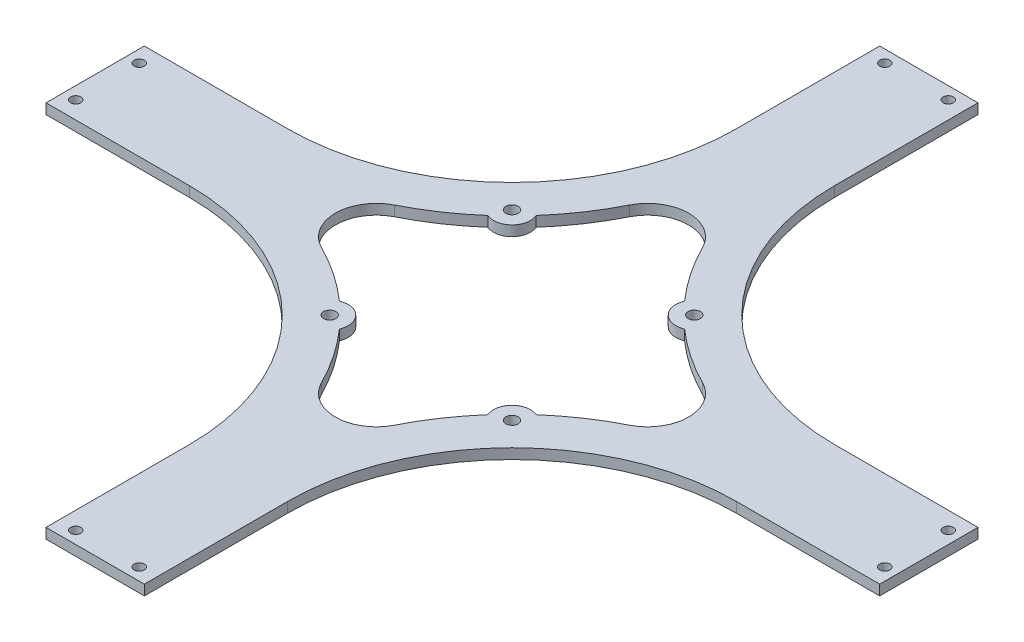
SolidWorks part; units mm, degrees
material "Chipboard"
ref_plane "Front Plane" through (0, 0, 0) normal (0, 0, 1) x (1, 0, 0)
ref_plane "Top Plane" through (0, 0, 0) normal (0, 1, 0) x (1, 0, 0)
ref_plane "Right Plane" through (0, 0, 0) normal (1, 0, 0) x (0, 0, -1)
sketch "Sketch1" plane through (0, 0, 0) normal (0, 1, 0) x (1, 0, 0)
  line L0 (0, 101.75) -> (0, -101.75) construction
  line L1 (-12, 101.75) -> (-12, 66.75)
  line L2 (12, 101.75) -> (12, 66.75)
  line L3 (-101.75, 0) -> (101.75, 0) construction
  line L4 (-101.75, -12) -> (-66.75, -12)
  line L6 (12, 101.75) -> (-12, 101.75)
  line L7 (-12, -66.75) -> (-12, -101.75)
  line L9 (-12, 101.75) -> (-12, -101.75) construction
  line L10 (12, -66.75) -> (12, -101.75)
  line L11 (-101.75, -12) -> (101.75, -12) construction
  line L13 (12, 101.75) -> (12, -101.75) construction
  line L14 (12, 98.75) -> (-12, 98.75) construction
  line L16 (-7.75, 101.75) -> (-7.75, 98.75) construction
  line L17 (7.75, 101.75) -> (7.75, 98.75) construction
  line L18 (7.75, -101.75) -> (7.75, -98.75) construction
  line L19 (-7.75, -101.75) -> (-7.75, -98.75) construction
  line L20 (-7.75, 101.75) -> (-7.75, -101.75) construction
  line L21 (12, -98.75) -> (-12, -98.75) construction
  line L22 (7.75, 101.75) -> (7.75, -101.75) construction
  line L23 (12, -101.75) -> (-12, -101.75)
  line L24 (101.75, 12) -> (66.75, 12)
  line L25 (101.75, -12) -> (66.75, -12)
  line L26 (101.75, -12) -> (101.75, 12)
  line L27 (-66.75, 12) -> (-101.75, 12)
  line L28 (-66.75, -12) -> (-101.75, -12)
  line L29 (-101.75, -12) -> (-101.75, 12)
  line L30 (101.75, 0) -> (-101.75, 0) construction
  line L31 (98.75, -12) -> (98.75, 12) construction
  line L32 (101.75, 7.75) -> (98.75, 7.75) construction
  line L33 (101.75, -7.75) -> (98.75, -7.75) construction
  line L34 (-101.75, -7.75) -> (-98.75, -7.75) construction
  line L35 (-101.75, 7.75) -> (-98.75, 7.75) construction
  line L36 (-98.75, -12) -> (-98.75, 12) construction
  line L37 (-66.75, -12) -> (-66.75, 12) construction
  line L38 (12, -66.75) -> (-12, -66.75) construction
  line L39 (66.75, -12) -> (66.75, 12) construction
  line L40 (12, 66.75) -> (-12, 66.75) construction
  circle A0 centre (-7.75, 98.75) radius 1.25
  circle A1 centre (7.75, 98.75) radius 1.25
  circle A2 centre (7.75, -98.75) radius 1.25
  circle A3 centre (-7.75, -98.75) radius 1.25
  circle A4 centre (98.75, 7.75) radius 1.25
  circle A5 centre (98.75, -7.75) radius 1.25
  circle A6 centre (-98.75, -7.75) radius 1.25
  circle A7 centre (-98.75, 7.75) radius 1.25
  arc A8 (-12, -66.75) -> (-66.75, -12) centre (-66.75, -66.75) ccw
  arc A9 (-66.75, 12) -> (-12, 66.75) centre (-66.75, 66.75) ccw
  arc A10 (12, 66.75) -> (66.75, 12) centre (66.75, 66.75) ccw
  arc A11 (66.75, -12) -> (12, -66.75) centre (66.75, -66.75) ccw
  arc A12 (-8.9298, -37.6058) -> (-37.6058, -8.9298) centre (-66.75, -66.75) ccw
  arc A13 (-37.6058, 8.9298) -> (-8.9298, 37.6058) centre (-66.75, 66.75) ccw
  arc A14 (37.6058, -8.9298) -> (8.9298, -37.6058) centre (66.75, -66.75) ccw
  arc A15 (8.9298, 37.6058) -> (37.6058, 8.9298) centre (66.75, 66.75) ccw
  arc A16 (-37.6058, 8.9298) -> (-37.6058, -8.9298) centre (-33.1048, 0) ccw
  arc A17 (8.9298, 37.6058) -> (-8.9298, 37.6058) centre (0, 33.1048) ccw
  arc A18 (-2, -66.75) -> (-66.75, -2) centre (-66.75, -66.75) ccw construction
  arc A19 (-66.75, 2) -> (-2, 66.75) centre (-66.75, 66.75) ccw construction
  arc A20 (37.6058, -8.9298) -> (37.6058, 8.9298) centre (33.1048, 0) ccw
  arc A21 (2, 66.75) -> (66.75, 2) centre (66.75, 66.75) ccw construction
  arc A22 (-8.9298, -37.6058) -> (8.9298, -37.6058) centre (0, -33.1048) ccw
  arc A23 (66.75, -2) -> (2, -66.75) centre (66.75, -66.75) ccw construction
  point P7 (0, 0)
  point P10 (0, 0)
  point P13 (-101.75, 12)
  point P14 (101.75, 12)
  point P66 (0, 0)
  dimension "D10" = 2
  dimension "D1" = 203.5
  dimension "D4" = 203.5
  dimension "D6" = 12
  dimension "D15" = 10
  dimension "D2" = 12
  dimension "D3" = 12
  dimension "D5" = 12
  dimension "D7" = 3
  dimension "D8" = 7.75
  dimension "D9" = 7.75
  dimension "D11" = 35
  dimension "D12" = 35
  dimension "D13" = 35
  dimension "D14" = 35
extrude "Boss-Extrude1" add sketch "Sketch1" along normal blind 2.5
sketch "Sketch2" plane through (0, 2.5, 0) normal (0, 1, 0) x (1, 0, 0)
  line L0 (-28.0359, 28.0359) -> (28.0359, -28.0359) construction
  line L1 (-28.0359, -28.0359) -> (28.0359, 28.0359) construction
  line L2 (-22.25, 22.25) -> (-22.25, -22.25) construction
  line L3 (-22.25, 22.25) -> (22.25, 22.25) construction
  line L4 (22.25, 22.25) -> (22.25, -22.25) construction
  line L5 (22.25, -22.25) -> (-22.25, -22.25) construction
  arc A0 (-66.75, 12) -> (-12, 66.75) centre (-66.75, 66.75) ccw construction
  arc A1 (66.75, -12) -> (12, -66.75) centre (66.75, -66.75) ccw construction
  arc A2 (-12, -66.75) -> (-66.75, -12) centre (-66.75, -66.75) ccw construction
  arc A3 (12, 66.75) -> (66.75, 12) centre (66.75, 66.75) ccw construction
  circle A4 centre (-22.25, -22.25) radius 1.5
  circle A5 centre (-22.25, 22.25) radius 1.5
  circle A6 centre (22.25, 22.25) radius 1.5
  circle A7 centre (22.25, -22.25) radius 1.5
  circle A8 centre (-22.25, -22.25) radius 4.5
  circle A9 centre (-22.25, 22.25) radius 4.5
  circle A10 centre (22.25, 22.25) radius 4.5
  circle A11 centre (22.25, -22.25) radius 4.5
  arc A12 (-37.6058, 8.9298) -> (-8.9298, 37.6058) centre (-66.75, 66.75) ccw construction
  arc A13 (-37.6058, 8.9298) -> (-8.9298, 37.6058) centre (-66.75, 66.75) ccw
  arc A14 (8.9298, 37.6058) -> (37.6058, 8.9298) centre (66.75, 66.75) ccw construction
  arc A15 (8.9298, 37.6058) -> (37.6058, 8.9298) centre (66.75, 66.75) ccw
  arc A16 (37.6058, -8.9298) -> (8.9298, -37.6058) centre (66.75, -66.75) ccw construction
  arc A17 (37.6058, -8.9298) -> (8.9298, -37.6058) centre (66.75, -66.75) ccw
  arc A18 (-8.9298, -37.6058) -> (-37.6058, -8.9298) centre (-66.75, -66.75) ccw construction
  arc A19 (-8.9298, -37.6058) -> (-37.6058, -8.9298) centre (-66.75, -66.75) ccw
  arc M8 (-8.9298, -37.6058) -> (-37.6058, -8.9298) centre (-66.75, -66.75) ccw
  arc M10 (-37.6058, 8.9298) -> (-8.9298, 37.6058) centre (-66.75, 66.75) ccw
  arc M12 (8.9298, 37.6058) -> (37.6058, 8.9298) centre (66.75, 66.75) ccw
  arc M14 (37.6058, -8.9298) -> (8.9298, -37.6058) centre (66.75, -66.75) ccw
  dimension "D3" = 3
  dimension "D4" = 3
  dimension "D5" = 3
  dimension "D6" = 3
  dimension "D1" = 44.5
  dimension "D2" = 45
  dimension "D7" = 3
  dimension "D8" = 3
extrude "Boss-Extrude2" add sketch "Sketch2" against normal blind 2.5 contours A8 M8 | A9 M10 | A10 M12 | A11 M14
sketch "Sketch3" plane through (0, 2.5, 0) normal (0, 1, 0) x (1, 0, 0)
  arc A0 (-8.9298, -37.6058) -> (-37.6058, -8.9298) centre (-66.75, -66.75) ccw construction
  circle A1 centre (22.25, -22.25) radius 4.5
  circle A2 centre (22.25, -22.25) radius 4.5
  circle A3 centre (22.25, 22.25) radius 4.5
  circle A4 centre (22.25, 22.25) radius 4.5
  circle A5 centre (-22.25, 22.25) radius 4.5
  circle A6 centre (-22.25, 22.25) radius 4.5
  circle A7 centre (-22.25, -22.25) radius 4.5
  circle A8 centre (-22.25, -22.25) radius 4.5
  circle A9 centre (22.25, -22.25) radius 1.5
  circle A10 centre (22.25, -22.25) radius 1.5
  circle A11 centre (22.25, 22.25) radius 1.5
  circle A12 centre (22.25, 22.25) radius 1.5
  circle A13 centre (-22.25, 22.25) radius 1.5
  circle A14 centre (-22.25, 22.25) radius 1.5
  circle A15 centre (-22.25, -22.25) radius 1.5
  circle A16 centre (-22.25, -22.25) radius 1.5
  arc A17 (37.6058, -8.9298) -> (8.9298, -37.6058) centre (66.75, -66.75) ccw construction
  arc A18 (8.9298, 37.6058) -> (37.6058, 8.9298) centre (66.75, 66.75) ccw construction
  arc A19 (-37.6058, 8.9298) -> (-8.9298, 37.6058) centre (-66.75, 66.75) ccw construction
  arc A20 (-8.9298, -37.6058) -> (-37.6058, -8.9298) centre (-66.75, -66.75) ccw
  arc A21 (37.6058, -8.9298) -> (8.9298, -37.6058) centre (66.75, -66.75) ccw
  arc A22 (8.9298, 37.6058) -> (37.6058, 8.9298) centre (66.75, 66.75) ccw
  arc A23 (-37.6058, 8.9298) -> (-8.9298, 37.6058) centre (-66.75, 66.75) ccw
  dimension "D1" = 0
  dimension "D2" = 0
  dimension "D3" = 0
  dimension "D4" = 0
  dimension "D5" = 0
  dimension "D6" = 0
  dimension "D7" = 0
  dimension "D8" = 0
extrude "Cut-Extrude1" cut sketch "Sketch3" against normal blind 2.5 contours A14 | A12 | A10 | A16
